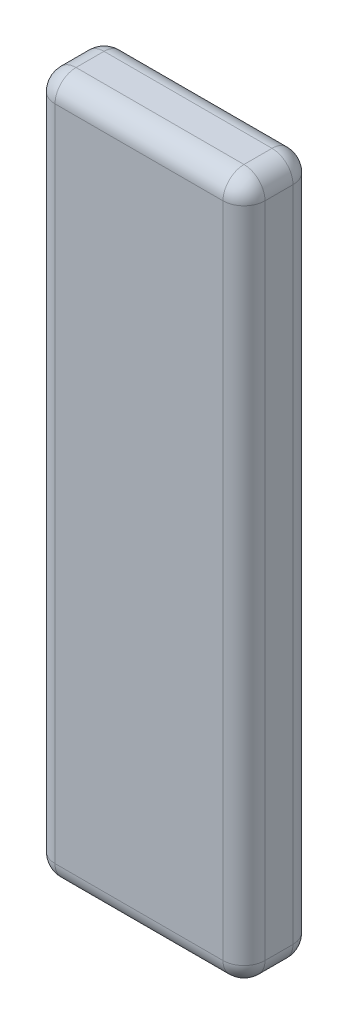
SolidWorks part; units mm, degrees
ref_plane "Ebene vorne" through (0, 0, 0) normal (0, 0, 1) x (1, 0, 0)
ref_plane "Ebene oben" through (0, 0, 0) normal (0, 1, 0) x (1, 0, 0)
ref_plane "Ebene rechts" through (0, 0, 0) normal (1, 0, 0) x (0, 0, -1)
sketch "Skizze1" plane through (0, 0, 0) normal (0, 0, 1) x (1, 0, 0)
  line L1 (0, 0) -> (6, 0)
  line L2 (0, 0) -> (0, -20)
  line L3 (0, -20) -> (6, -20)
  line L4 (6, 0) -> (6, -20)
  dimension "D1" = 20
  dimension "D2" = 6
extrude "Aufsatz-Linear austragen1" add sketch "Skizze1" along normal blind 2
fillet "Verrundung1" radius 0.6 12 edges at (0, 0, 1) (3, 0, 0) (0, -10, 0) (0, -20, 1) (3, -20, 0) (6, -20, 1) (6, 0, 1) (6, -10, 0) (3, 0, 2) (6, -10, 2) (3, -20, 2) (0, -10, 2)
